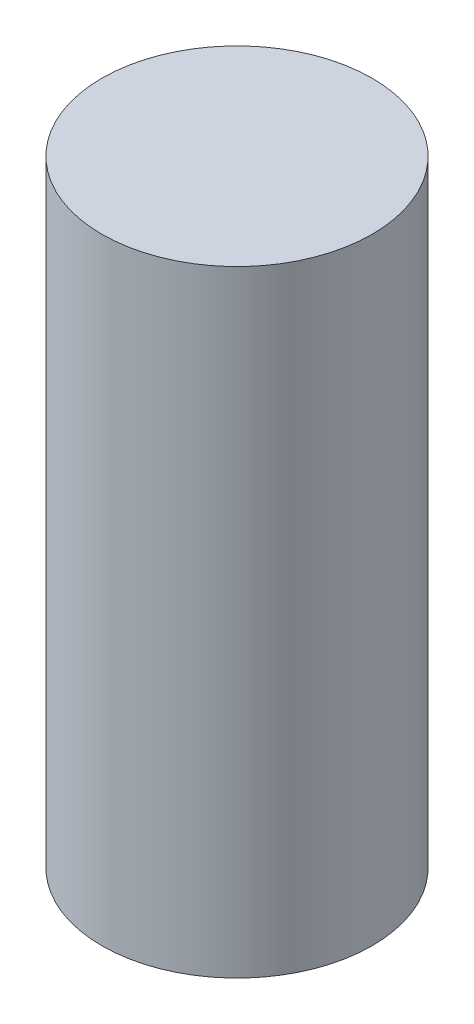
SolidWorks part; units mm, degrees
ref_plane "Front" through (0, 0, 0) normal (0, 0, 1) x (1, 0, 0)
ref_plane "Top" through (0, 0, 0) normal (0, 1, 0) x (1, 0, 0)
ref_plane "Right" through (0, 0, 0) normal (1, 0, 0) x (0, 0, -1)
sketch "Sketch1" plane through (0, 0, 0) normal (0, 1, 0) x (1, 0, 0)
  circle A0 centre (0, 0) radius 329
  dimension "D1" = 658
extrude "Boss-Extrude1" add sketch "Sketch1" along normal blind 1500
equation "\"Height\"= 1500"
equation "\"D1@Boss-Extrude1\"=\"Height\""
